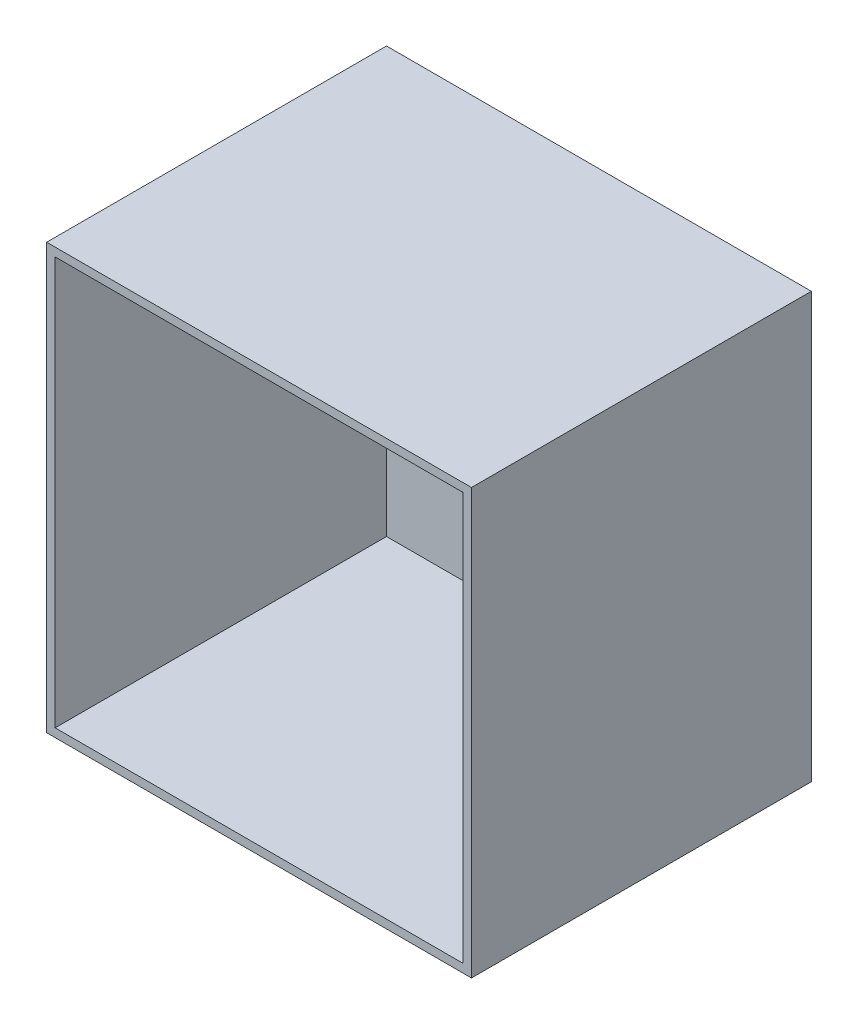
SolidWorks part; units mm, degrees
ref_plane "前视基准面" through (0, 0, 0) normal (0, 0, 1) x (1, 0, 0)
ref_plane "上视基准面" through (0, 0, 0) normal (0, 1, 0) x (1, 0, 0)
ref_plane "右视基准面" through (0, 0, 0) normal (1, 0, 0) x (0, 0, -1)
other "Configuration Table"
sketch "草图1" plane through (0, 0, 0) normal (0, 0, 1) x (1, 0, 0)
  line L1 (0, 0) -> (150, 0)
  line L2 (0, 0) -> (0, -150)
  line L3 (0, -150) -> (150, -150)
  line L4 (150, 0) -> (150, -150)
  dimension "D1" = 150
  dimension "D2" = 150
extrude "凸台-拉伸1" add sketch "草图1" along normal blind 120
shell "抽壳1" thickness 3
